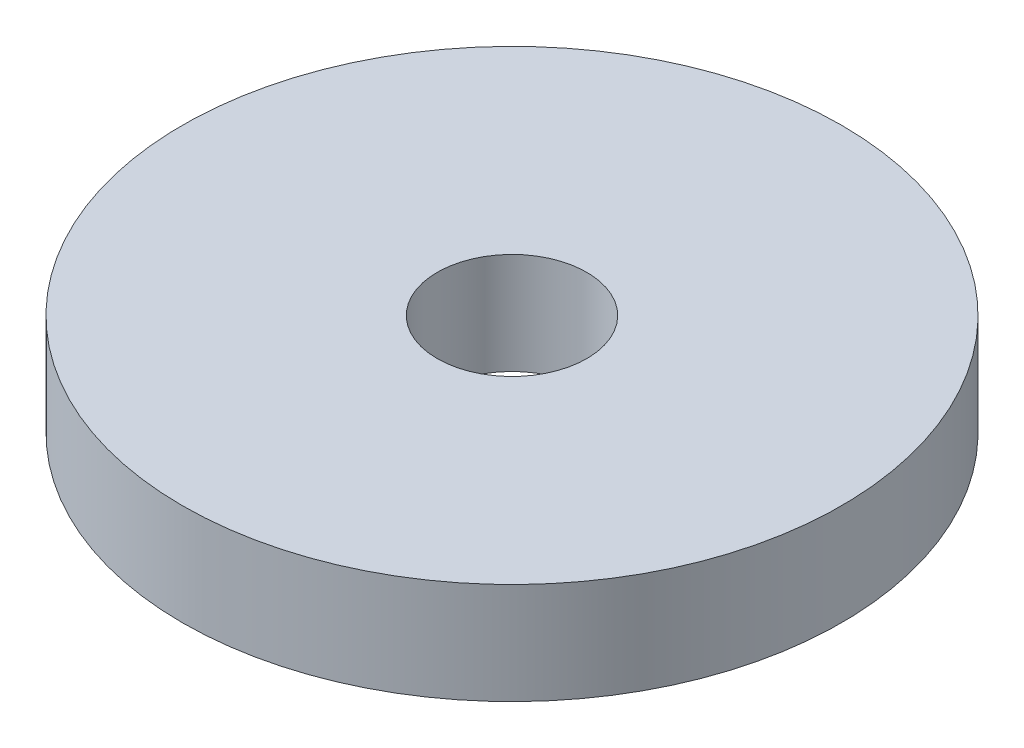
SolidWorks part; units mm, degrees
ref_plane "Front Plane" through (0, 0, 0) normal (0, 0, 1) x (1, 0, 0)
ref_plane "Top Plane" through (0, 0, 0) normal (0, 1, 0) x (1, 0, 0)
ref_plane "Right Plane" through (0, 0, 0) normal (1, 0, 0) x (0, 0, -1)
sketch "Sketch1" plane through (0, 0, 0) normal (0, 1, 0) x (1, 0, 0)
  circle A0 centre (0, 0) radius 6.5
  circle A1 centre (0, 0) radius 1.475
  dimension "D1" = 13
  dimension "D2" = 2.95
extrude "Boss-Extrude1" add sketch "Sketch1" along normal blind 2
